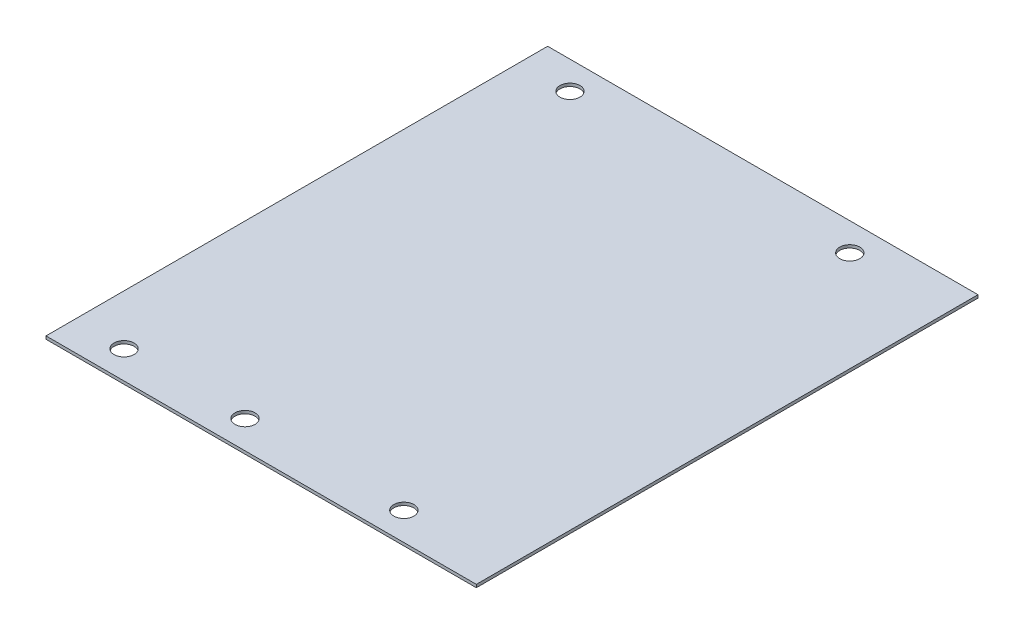
SolidWorks part; units mm, degrees
ref_plane "Alzado" through (0, 0, 0) normal (0, 0, 1) x (1, 0, 0)
ref_plane "Planta" through (0, 0, 0) normal (0, 1, 0) x (1, 0, 0)
ref_plane "Vista lateral" through (0, 0, 0) normal (1, 0, 0) x (0, 0, -1)
sketch "Croquis1" plane through (0, 0, 0) normal (0, 1, 0) x (1, 0, 0)
  line L1 (193, -225) -> (-193, -225)
  line L2 (193, -225) -> (193, 225)
  line L3 (193, 225) -> (-193, 225)
  line L4 (-193, -225) -> (-193, 225)
  line L5 (193, -225) -> (-193, 225) construction
  line L6 (193, 225) -> (-193, -225) construction
  point P0 (0, 0)
  dimension "D1" = 386
  dimension "D2" = 450
extrude "Saliente-Extruir1" add sketch "Croquis1" along normal blind 2.66
sketch "Croquis2" plane through (0, 2.66, 0) normal (0, 1, 0) x (1, 0, 0)
  line L0 (193, 225) -> (-193, 225) construction
  line L1 (193, -225) -> (193, 225) construction
  line L2 (-193, -225) -> (193, -225) construction
  circle A0 centre (-148, 200) radius 9
  circle A1 centre (103, 200) radius 9
  circle A2 centre (-148, -200) radius 9
  circle A3 centre (-39.5, -200) radius 9
  circle A4 centre (103, -200) radius 9
  dimension "D1" = 18
  dimension "D3" = 18
  dimension "D9" = 18
  dimension "D10" = 18
  dimension "D14" = 18
  dimension "D2" = 25
  dimension "D4" = 25
  dimension "D5" = 251
  dimension "D6" = 90
  dimension "D7" = 25
  dimension "D8" = 251
  dimension "D11" = 90
  dimension "D12" = 25
  dimension "D13" = 142.5
  dimension "D15" = 25
extrude "Cortar-Extruir1" cut sketch "Croquis2" against normal blind 3
